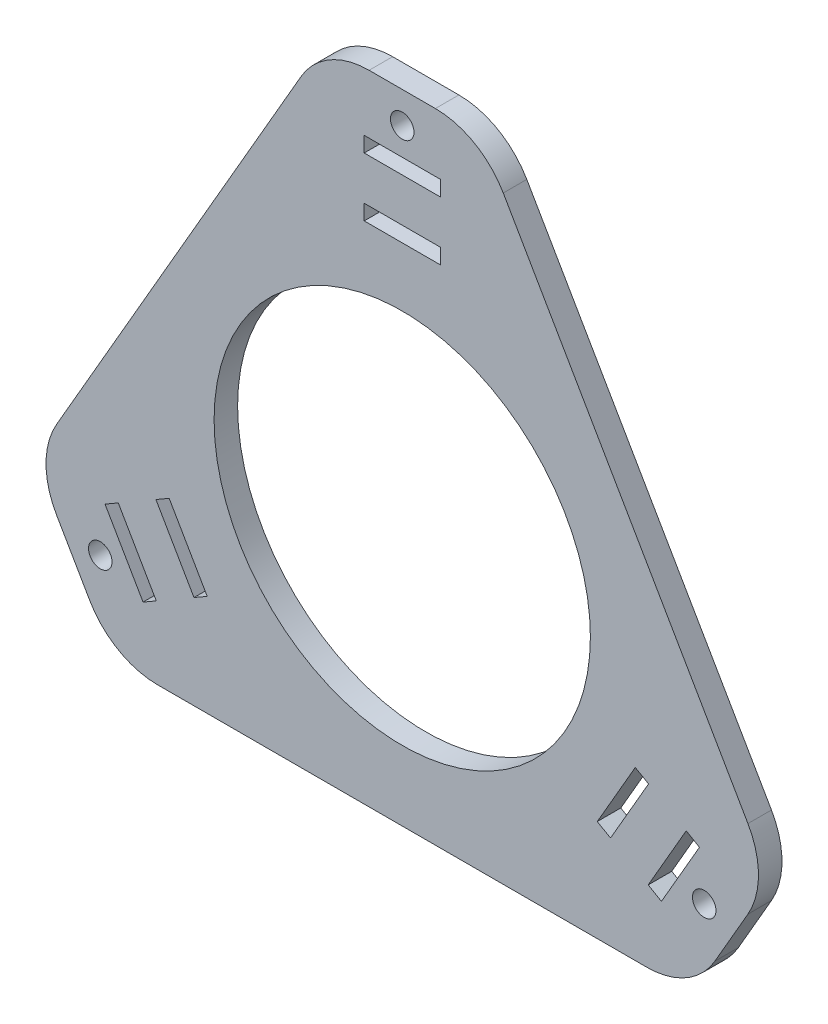
SolidWorks part; units mm, degrees
ref_plane "Спереди" through (0, 0, 0) normal (0, 0, 1) x (1, 0, 0)
ref_plane "Сверху" through (0, 0, 0) normal (0, 1, 0) x (1, 0, 0)
ref_plane "Справа" through (0, 0, 0) normal (1, 0, 0) x (0, 0, -1)
other "Configuration Table"
sketch "Эскиз1" plane through (0, 0, 0) normal (0, 0, 1) x (1, 0, 0)
  line L0 (0, 0) -> (-69.282, -40) construction
  line L1 (-31.2071, -32.8978) -> (31.2071, -32.8978)
  line L2 (44.0938, -10.5772) -> (12.8868, 43.475)
  line L3 (-12.8868, 43.475) -> (-44.0938, -10.5772)
  line L4 (-33.0604, -24.6877) -> (-37.9104, -16.2873)
  line L6 (-44.0938, -20.5772) -> (-39.8673, -27.8978)
  line L7 (44.0938, -20.5772) -> (39.8673, -27.8978)
  line L8 (4.2265, 48.475) -> (-4.2265, 48.475)
  line L12 (0, 0) -> (41.9806, -24.2375) construction
  line L13 (-33.0604, -24.6877) -> (-31.3716, -23.7127)
  line L14 (-37.9104, -16.2873) -> (-36.2216, -15.3123)
  line L15 (-31.3716, -23.7127) -> (-36.2216, -15.3123)
  line L16 (-33.0604, -24.6877) -> (-36.2216, -15.3123) construction
  line L17 (-37.9104, -16.2873) -> (-31.3716, -23.7127) construction
  line L18 (-4.85, 40.975) -> (-4.85, 39.025)
  line L19 (4.85, 39.025) -> (-4.85, 39.025)
  line L20 (4.85, 40.975) -> (4.85, 39.025)
  line L21 (4.85, 40.975) -> (-4.85, 40.975)
  line L22 (37.9104, -16.2873) -> (33.0604, -24.6877)
  line L23 (37.9104, -16.2873) -> (36.2216, -15.3123)
  line L24 (36.2216, -15.3123) -> (31.3716, -23.7127)
  line L25 (33.0604, -24.6877) -> (31.3716, -23.7127)
  line L26 (-26.5652, -20.9377) -> (-31.4152, -12.5373)
  line L27 (-26.5652, -20.9377) -> (-24.8765, -19.9627)
  line L28 (-31.4152, -12.5373) -> (-29.7265, -11.5623)
  line L29 (-24.8765, -19.9627) -> (-29.7265, -11.5623)
  line L30 (4.85, 33.475) -> (4.85, 31.525)
  line L31 (4.85, 31.525) -> (-4.85, 31.525)
  line L32 (-4.85, 33.475) -> (-4.85, 31.525)
  line L33 (4.85, 33.475) -> (-4.85, 33.475)
  line L34 (31.4152, -12.5373) -> (26.5652, -20.9377)
  line L35 (26.5652, -20.9377) -> (24.8765, -19.9627)
  line L36 (29.7265, -11.5623) -> (24.8765, -19.9627)
  line L37 (31.4152, -12.5373) -> (29.7265, -11.5623)
  circle A0 centre (0, 0) radius 32.8978 construction
  circle A1 centre (-38.5165, -22.2375) radius 1.5
  circle A2 centre (0, 44.475) radius 1.5
  circle A3 centre (38.5165, -22.2375) radius 1.5
  circle A4 centre (0, 0) radius 24
  arc A5 (-31.2071, -32.8978) -> (-39.8673, -27.8978) centre (-31.2071, -22.8978) cw
  arc A6 (-44.0938, -20.5772) -> (-44.0938, -10.5772) centre (-35.4336, -15.5772) cw
  arc A7 (-4.2265, 48.475) -> (-12.8868, 43.475) centre (-4.2265, 38.475) ccw
  arc A8 (4.2265, 48.475) -> (12.8868, 43.475) centre (4.2265, 38.475) cw
  arc A9 (44.0938, -10.5772) -> (44.0938, -20.5772) centre (35.4336, -15.5772) cw
  arc A10 (39.8673, -27.8978) -> (31.2071, -32.8978) centre (31.2071, -22.8978) cw
  point P4 (-34.641, -20)
  point P9 (-41.9806, -24.2375)
  point P16 (-36.9806, -32.8978)
  point P49 (-46.9806, -15.5772)
  point P52 (-10, 48.475)
  point P55 (10, 48.475)
  point P58 (46.9806, -15.5772)
  point P61 (36.9806, -32.8978)
  dimension "D5" = 3
  dimension "D12" = 48
  dimension "D13" = 10
  dimension "D14" = 10
  dimension "D1" = 20
  dimension "D2" = 80
  dimension "D3" = 1.95
  dimension "D4" = 20
  dimension "D6" = 9.7
  dimension "D7" = 4
  dimension "D8" = 20
  dimension "D9" = 3.5
  dimension "D10" = 5.55
  dimension "D11" = 1.95
extrude "Бобышка-Вытянуть4" add sketch "Эскиз1" along normal blind 3
